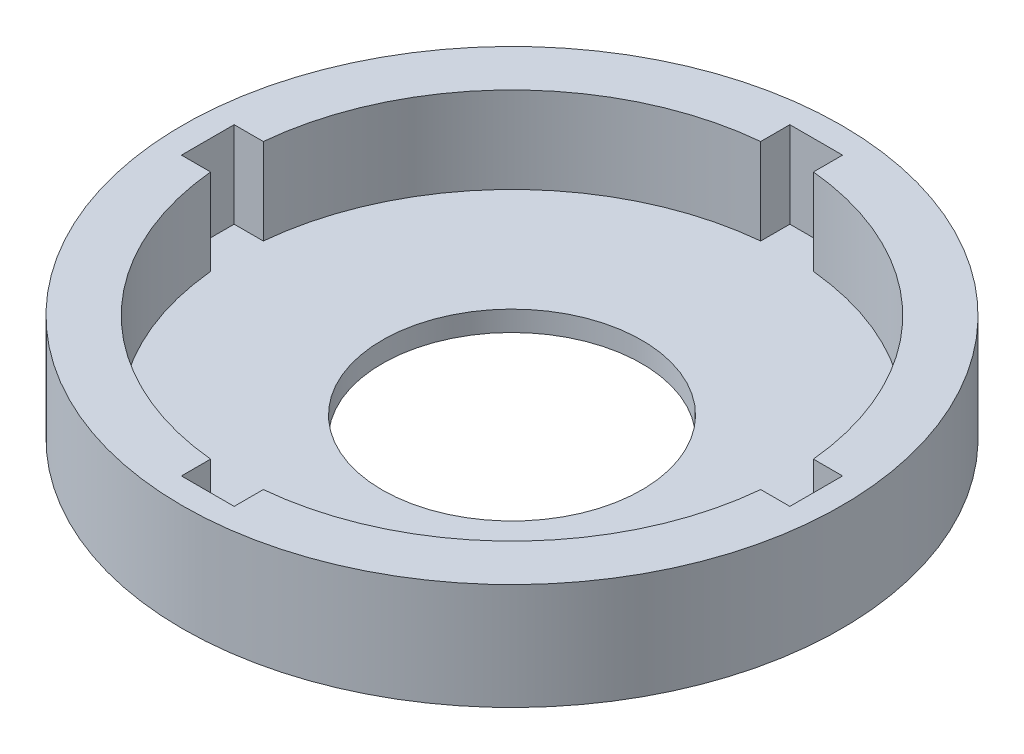
SolidWorks part; units mm, degrees
ref_plane "Front Plane" through (0, 0, 0) normal (0, 0, 1) x (1, 0, 0)
ref_plane "Top Plane" through (0, 0, 0) normal (0, 1, 0) x (1, 0, 0)
ref_plane "Right Plane" through (0, 0, 0) normal (1, 0, 0) x (0, 0, -1)
sketch "Sketch1" plane through (0, 0, 0) normal (0, 1, 0) x (1, 0, 0)
  circle A0 centre (0, 0) radius 32.5
  circle A1 centre (0, 0) radius 12.8
  dimension "D1" = 65
  dimension "D2" = 25.6
extrude "Boss-Extrude1" add sketch "Sketch1" along normal blind 2
sketch "Sketch2" plane through (0, 2, 0) normal (0, 1, 0) x (1, 0, 0)
  line L0 (0, -55) -> (0, 55) construction
  line L1 (2.6, -30) -> (-2.6, -30)
  line L2 (2.6, -30) -> (2.6, -26.0456)
  line L3 (2.6, -26.0456) -> (-2.6, -26.0456)
  line L4 (-2.6, -30) -> (-2.6, -26.0456)
  line L5 (2.6, -30) -> (-2.6, -26.0456) construction
  line L6 (2.6, -26.0456) -> (-2.6, -30) construction
  line L7 (-30, -2.6) -> (-30, 2.6)
  line L8 (-30, -2.6) -> (-26.0456, -2.6)
  line L9 (-30, 2.6) -> (-26.0456, 2.6)
  line L10 (-26.0456, -2.6) -> (-26.0456, 2.6)
  line L11 (-2.6, 30) -> (2.6, 30)
  line L12 (-2.6, 30) -> (-2.6, 26.0456)
  line L13 (2.6, 30) -> (2.6, 26.0456)
  line L14 (-2.6, 26.0456) -> (2.6, 26.0456)
  line L15 (30, 2.6) -> (30, -2.6)
  line L16 (30, 2.6) -> (26.0456, 2.6)
  line L17 (30, -2.6) -> (26.0456, -2.6)
  line L18 (26.0456, 2.6) -> (26.0456, -2.6)
  circle A0 centre (0, 0) radius 27.1
  circle A1 centre (0, 0) radius 27.25
  circle A2 centre (0, 0) radius 32.5
  point P4 (0, -28.0228)
  circle M7 centre (0, 0) radius 32.5
  dimension "D1" = 54.5
  dimension "D2" = 54.2
  dimension "D3" = 30
  dimension "D4" = 5.2
  dimension "D5" = 4
extrude "Boss-Extrude2" add sketch "Sketch2" along normal blind 8.5 contours A0 L2 L1 L4 L8 L7 L9 L12 L11 L13 L16 L15 L17 M7
